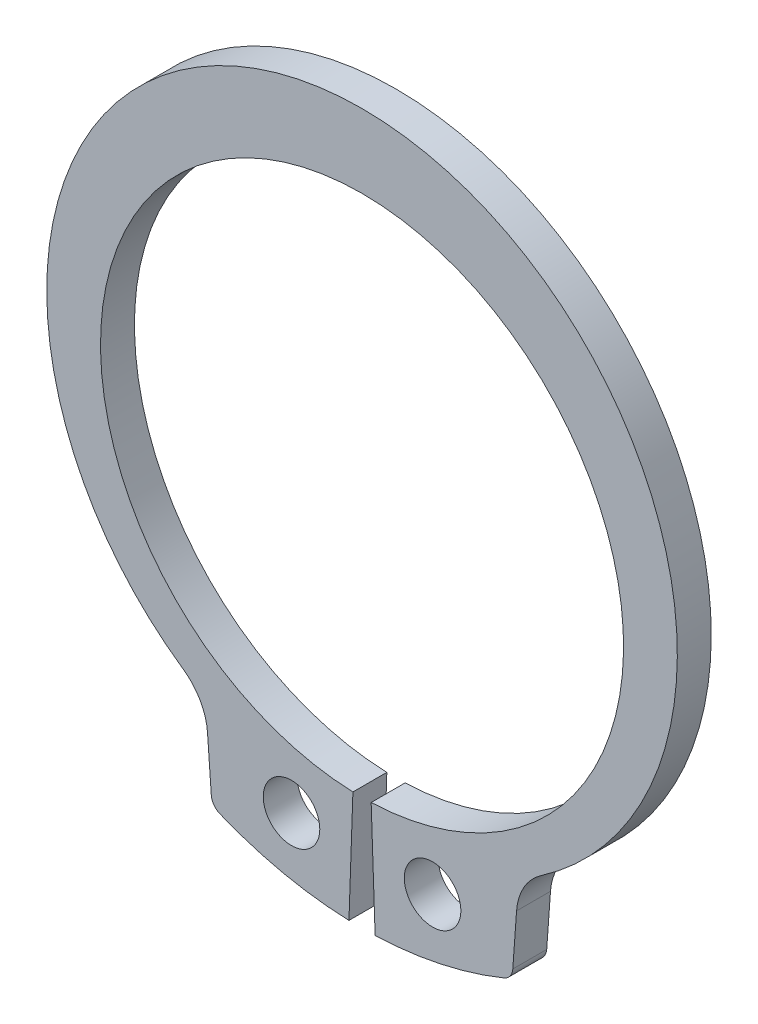
SolidWorks part; units mm, degrees
ref_plane "Front" through (0, 0, 0) normal (0, 0, 1) x (1, 0, 0)
ref_plane "Top" through (0, 0, 0) normal (0, 1, 0) x (1, 0, 0)
ref_plane "Right" through (0, 0, 0) normal (1, 0, 0) x (0, 0, -1)
sketch "Sketch1" plane through (0, 0, 0) normal (0, 0, 1) x (1, 0, 0)
  line L0 (0, 0) -> (-8.0107, -4.625) construction
  line L1 (0, 13.25) -> (0, -13.25) construction
  line L2 (-5.3095, -12.1485) -> (-5.5385, -8.9793) construction
  line L4 (-5.5385, -8.9793) -> (-6.2209, -10.0858) construction
  line L5 (-5.5385, -8.9793) -> (0, 0) construction
  line L6 (0, 9.25) -> (0, 11.85) construction
  line L7 (0, 11.85) -> (0, 10.55) construction
  line L8 (0, -9.25) -> (0, -13.25) construction
  line L9 (-2.9382, -12.9284) -> (0, 0) construction
  line L10 (0, 0) -> (-0.4627, -13.25) construction
  line L11 (-5.3095, -12.1485) -> (0, 0) construction
  line L12 (-5.4712, -9.9109) -> (-6.3289, -8.4819) construction
  line L13 (-5.9001, -9.1964) -> (-5.5385, -8.9793) construction
  line L14 (-2.0499, -9.02) -> (-2.9382, -12.9284) construction
  line L15 (-2.4941, -10.9742) -> (-1.5189, -11.1958) construction
  arc A0 (0, 11.85) -> (-5.5385, -8.9793) centre (0, 0.699) ccw construction
  circle A2 centre (0, 0) radius 11.85 construction
  arc A3 (-5.3095, -12.1485) -> (-0.4627, -13.25) centre (0, 0) ccw construction
  circle A4 centre (0, 0) radius 9.25 construction
  circle A6 centre (-2.4941, -10.9742) radius 1 construction
  arc A7 (-6.3289, -8.4819) -> (-5.4712, -9.9109) centre (-7.472, -10.1399) cw construction
  circle A9 centre (0, 0) radius 10 construction
  circle A10 centre (0, 0) radius 9.5 construction
  point P5 (-8.0107, -4.625)
  point P24 (-4.7456, -10.8582)
  point P35 (0, 11.85)
  point P36 (0, 9.25)
  point P37 (0, -9.25)
  point P38 (0, -13.25)
  dimension "Hole Diameter" = 2
  dimension "D10" = 2.0139
  dimension "For OD" = 20
  dimension "ID" = 18.5
  dimension "Max Sec." = 2.6
  dimension "Lug Height" = 4
  dimension "D6" = 2
  dimension "D5" = 3.1774
  dimension "D8" = 1.6667
  dimension "D3" = 120
  dimension "D2" = 5
  dimension "D4" = 1.6667
sketch "Sketch2" plane through (0, 0, 0) normal (-1, 0, 0) x (0, 1, 0)
  line L0 (-11.85, 0.6) -> (-11.85, -0.6) construction
  line L1 (11.85, -0.65) -> (11.85, 0.65) construction
  line L2 (0, 0.6) -> (0, -0.6) construction
  line L4 (-11.85, 0) -> (11.85, 0) construction
  point P3 (-11.85, 0)
  point P6 (0, 0)
  point P14 (11.85, 0)
  dimension "Thickness" = 1.2
  dimension "For Groove Width" = 1.3
sketch "Sketch4" plane through (0, 0, 0) normal (0, 0, 1) x (1, 0, 0)
  line L0 (-5.3095, -12.1485) -> (-5.5385, -8.9793) construction
  line L1 (-5.3095, -12.1485) -> (-5.5385, -8.9793)
  line L2 (0, 11.85) -> (0, 9.25)
  line L3 (-0.4627, -13.25) -> (-0.3228, -9.2444)
  line L4 (0, 0) -> (-0.4627, -13.25) construction
  arc A0 (0, 11.85) -> (-5.5385, -8.9793) centre (0, 0.699) ccw construction
  arc A1 (-5.3095, -12.1485) -> (-0.4627, -13.25) centre (0, 0) ccw construction
  circle A2 centre (-2.4941, -10.9742) radius 1 construction
  arc A4 (0, 11.85) -> (-5.5385, -8.9793) centre (0, 0.699) ccw
  arc A5 (-5.3095, -12.1485) -> (-0.4627, -13.25) centre (0, 0) ccw
  circle A6 centre (-2.4941, -10.9742) radius 1
  circle A7 centre (0, 0) radius 9.25 construction
  arc A8 (0, 9.25) -> (-0.3228, -9.2444) centre (0, 0) ccw
extrude "Boss-Extrude1" add sketch "Sketch4" along normal mid plane 1.2
fillet "Fillet1" radius 2.0139 1 edges at (-5.5385, -8.9793, 0)
fillet "Fillet2" radius 0.5035 1 edges at (-5.3095, -12.1485, 0)
mirror "Mirror1" about plane through (0, 11.85, 0.6) normal (-1, 0, 0) of bodies 109
sketch "Sketch3" plane through (0, 0, 0.6) normal (0, 0, 1) x (1, 0, 0)
  line L0 (5.5732, -7.3826) -> (6.3305, -8.4808) construction
  line L1 (6.3305, -8.4808) -> (7.4288, -7.7234) construction
  line L2 (0, 11.85) -> (0, 9.25) construction
  circle A0 centre (0, 0) radius 9.25 construction
  arc A1 (6.3305, -8.4808) -> (-6.3305, -8.4808) centre (0, 0.699) ccw construction
equation "\"D1@Fillet1\" = \"D10@Sketch1\""
equation "\"D1@Fillet2\" = \"D10@Sketch1\" / 4"
equation "\"Thickness@Boss-Extrude1\"  = \"Ring Thickness@Sketch5\""
equation "\"D2@Sketch1\"=\"Hole Diameter@Sketch1\"*2.5"
equation "\"D4@Sketch1\"=\"D2@Sketch1\"/3"
equation "\"D8@Sketch1\"=\"D4@Sketch1\""
